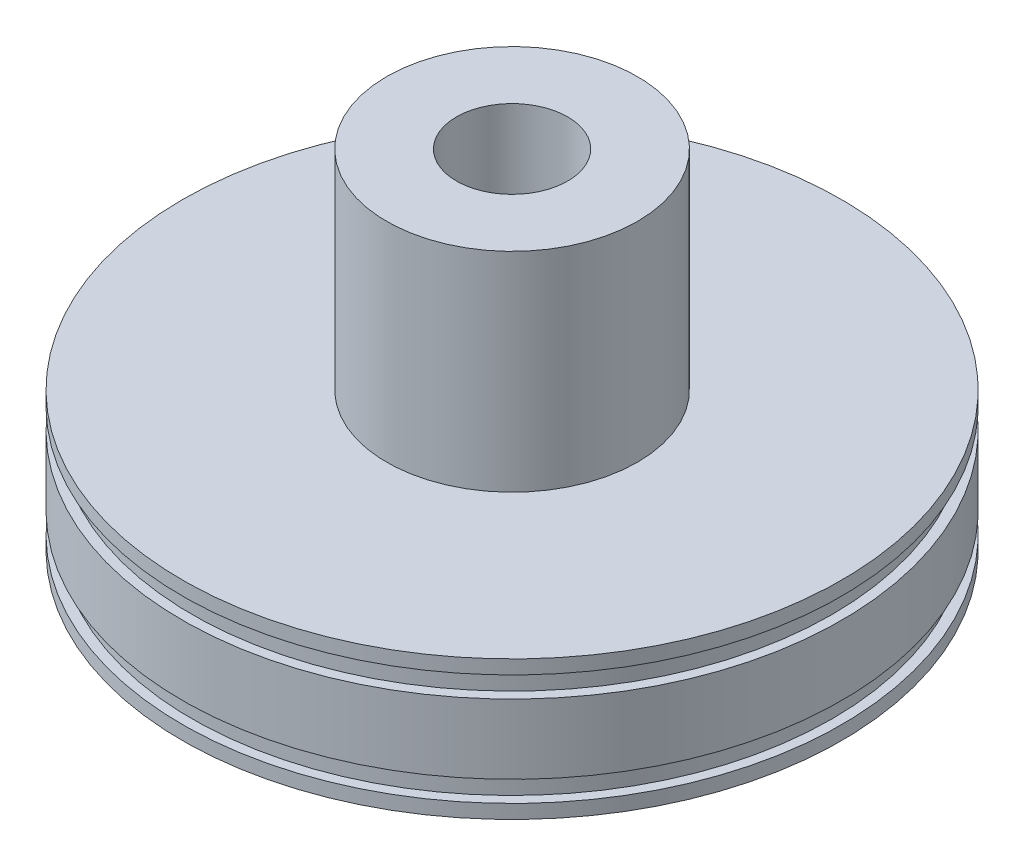
SolidWorks part; units mm, degrees
ref_plane "Front Plane" through (0, 0, 0) normal (0, 0, 1) x (1, 0, 0)
ref_plane "Top Plane" through (0, 0, 0) normal (0, 1, 0) x (1, 0, 0)
ref_plane "Right Plane" through (0, 0, 0) normal (1, 0, 0) x (0, 0, -1)
sketch "Sketch1" plane through (0, 0, 0) normal (0, 0, 1) x (1, 0, 0)
  line L0 (0, 0) -> (30.099, 18.0853)
  line L1 (0, 0) -> (23.0568, 0) construction
  line L2 (0, 19.05) -> (0, 0)
  line L3 (30.099, 18.0853) -> (30.099, 19.3553)
  line L4 (30.099, 30.7853) -> (0, 30.7853)
  line L5 (0, 30.7853) -> (0, 19.05)
  line L6 (30.099, 29.5153) -> (29.21, 29.5153)
  line L7 (29.21, 29.5153) -> (29.21, 27.6103)
  line L8 (29.21, 27.6103) -> (30.099, 27.6103)
  line L9 (30.099, 19.3553) -> (29.21, 19.3553)
  line L10 (29.21, 19.3553) -> (29.21, 21.2603)
  line L11 (29.21, 21.2603) -> (30.099, 21.2603)
  line L12 (30.099, 29.5153) -> (30.099, 30.7853)
  line L13 (30.099, 21.2603) -> (30.099, 27.6103)
  dimension "D1" = 31
  dimension "D2" = 19.05
  dimension "D3" = 30.099
  dimension "D4" = 1.27
  dimension "D5" = 1.905
  dimension "D6" = 29.21
  dimension "D7" = 1.27
  dimension "D8" = 1.905
  dimension "D9" = 12.7
revolve "Revolve1" add sketch "Sketch1" angle 360 about L5
sketch "Sketch2" plane through (0, 30.7853, 0) normal (0, 1, 0) x (1, 0, 0)
  circle A0 centre (0, 0) radius 11.4554
  dimension "D1" = 22.9108
extrude "Boss-Extrude1" add sketch "Sketch2" along normal blind 19.05
sketch "Sketch3" plane through (0, 49.8353, 0) normal (0, 1, 0) x (1, 0, 0)
  circle A0 centre (0, 0) radius 5.08
  dimension "D1" = 10.16
extrude "Cut-Extrude1" cut sketch "Sketch3" against normal blind 12.7
